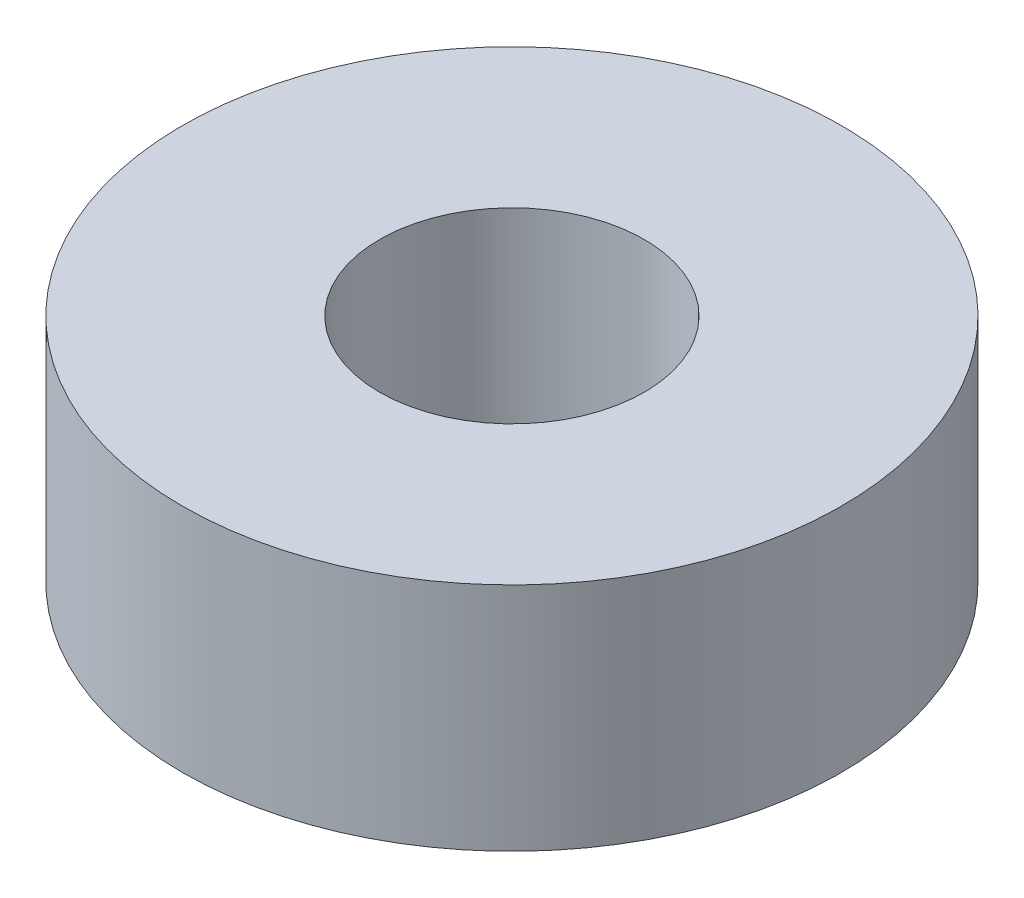
SolidWorks part; units mm, degrees
ref_plane "Front Plane" through (0, 0, 0) normal (0, 0, 1) x (1, 0, 0)
ref_plane "Top Plane" through (0, 0, 0) normal (0, 1, 0) x (1, 0, 0)
ref_plane "Right Plane" through (0, 0, 0) normal (1, 0, 0) x (0, 0, -1)
sketch "Sketch1" plane through (0, 0, 0) normal (0, 1, 0) x (1, 0, 0)
  circle A0 centre (0, 0) radius 6.35
  circle A1 centre (0, 0) radius 2.55
  dimension "D1" = 12.7
  dimension "D2" = 5.1
extrude "Boss-Extrude1" add sketch "Sketch1" along normal blind 4.445
